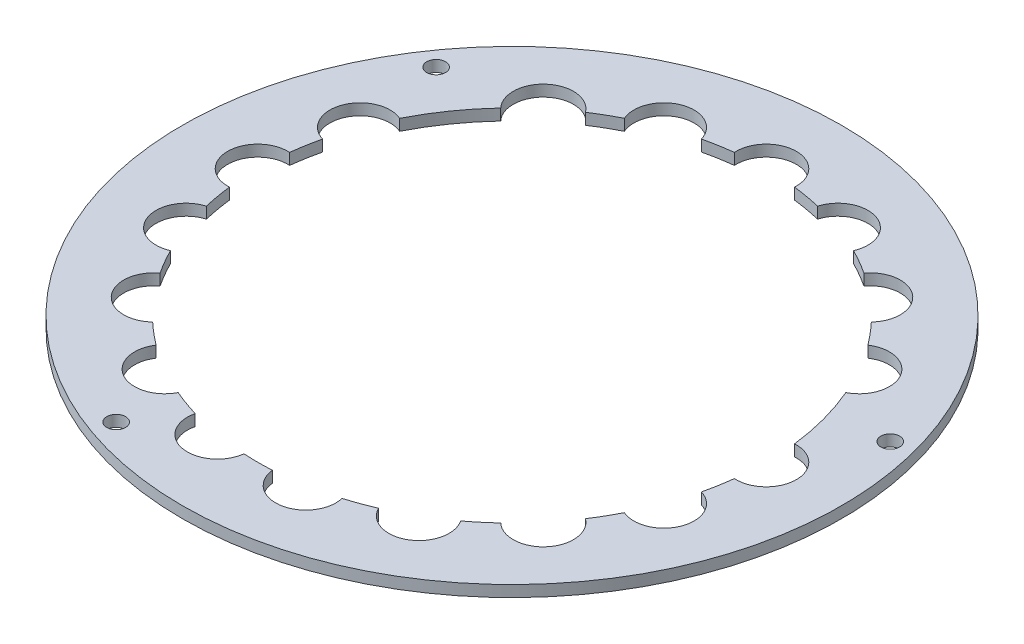
SolidWorks part; units mm, degrees
ref_plane "Front Plane" through (0, 0, 0) normal (0, 0, 1) x (1, 0, 0)
ref_plane "Top Plane" through (0, 0, 0) normal (0, 1, 0) x (1, 0, 0)
ref_plane "Right Plane" through (0, 0, 0) normal (1, 0, 0) x (0, 0, -1)
sketch "Sketch1" plane through (0, 0, 0) normal (0, 1, 0) x (1, 0, 0)
  circle A0 centre (0, 0) radius 17.5
  dimension "D1" = 35
extrude "Boss-Extrude1" add sketch "Sketch1" along normal blind 0.6
sketch "Sketch2" plane through (0, 0.6, 0) normal (0, 1, 0) x (1, 0, 0)
  circle A0 centre (0, 0) radius 13.5
  dimension "D1" = 27
extrude "Cut-Extrude1" cut sketch "Sketch2" against normal up to next
sketch "Sketch3" plane through (0, 0.6, 0) normal (0, 1, 0) x (1, 0, 0)
  line L0 (0, 0) -> (13.077, 7.55) construction
  line L1 (0, 0) -> (15.1, 0) construction
  circle A0 centre (0, 0) radius 15.1 construction
  circle A1 centre (11.6913, 6.75) radius 1.6
  dimension "D1" = 30.2
  dimension "D2" = 3.2
  dimension "D3" = 30
extrude "Cut-Extrude2" cut sketch "Sketch3" against normal up to next
pattern_circular "CirPattern1" count 6 every 20 about axis through (0, 0, 0) along (0, 1, 0) of "Cut-Extrude2"
sketch "Sketch4" plane through (0, 0.6, 0) normal (0, 1, 0) x (1, 0, 0)
  circle A0 centre (13.5, 0) radius 1.6
  arc A1 (-9.8402, 9.2423) -> (12.4078, 5.3194) centre (0, 0) ccw construction
  arc A2 (12.4078, 5.3194) -> (10.8106, 8.0858) centre (11.6913, 6.75) ccw construction
extrude "Cut-Extrude3" cut sketch "Sketch4" against normal up to next
pattern_circular "CirPattern2" count 11 every 20 about axis through (0, 0, 0) along (0, 1, 0) of "Cut-Extrude3"
hole_wizard "Ø1.0 (1) Diameter Hole1" positions "Sketch6" profile "Sketch5" hole size "Ø1.0" standard "DIN" end condition up to next
sketch "Sketch6" plane through (0, 0.6, 0) normal (0, 1, 0) x (1, 0, 0)
  line L0 (0, 0) -> (16.4, 0) construction
  line L1 (0, 0) -> (15.8412, 4.2446) construction
  line L2 (0, 0) -> (-5.6091, -15.411) construction
  line L4 (0, 0) -> (-13.4341, 9.4067) construction
  circle A0 centre (0, 0) radius 16.4 construction
  point P7 (15.8412, 4.2446)
  point P40 (-13.4341, 9.4067)
  point P44 (-5.6091, -15.411)
  dimension "D1" = 32.8
  dimension "D2" = 15
  dimension "D4" = 125
  dimension "D3" = 230
sketch "Sketch5" plane through (15.8412, 0.6, -4.2446) normal (1, 0, 0) x (0, 0, 1)
  line L0 (0, 0) -> (0, 0.6)
  line L1 (0, 0.6) -> (0.5, 0.6)
  line L2 (0.5, 0.6) -> (0.5, 0)
  line L5 (0.5, 0) -> (0, 0)
  line L11 (0, -6.35) -> (0, 107.95) construction
  dimension "Thru Hole Dia." = 1
  dimension "Thru Hole Depth" = 0.6
